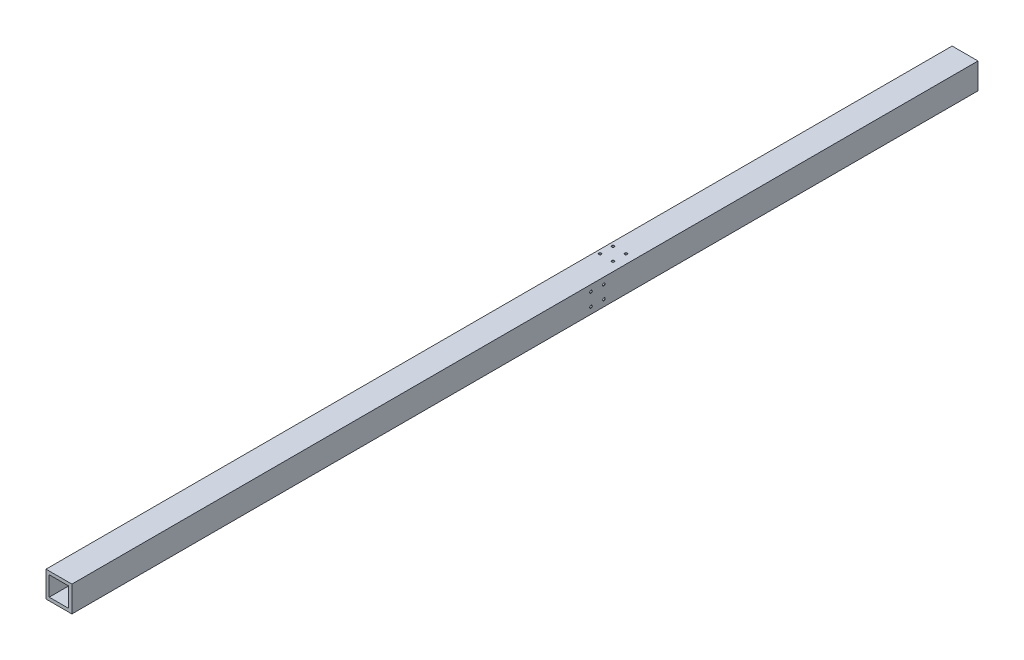
SolidWorks part; units mm, degrees
material "Д16Т ГОСТ 4784-74"
ref_plane "Спереди" through (0, 0, 0) normal (0, 0, 1) x (1, 0, 0)
ref_plane "Сверху" through (0, 0, 0) normal (0, 1, 0) x (1, 0, 0)
ref_plane "Справа" through (0, 0, 0) normal (1, 0, 0) x (0, 0, -1)
sketch "Эскиз1" plane through (0, 0, 0) normal (0, 0, 1) x (1, 0, 0)
  line L1 (0, 0) -> (40, 0)
  line L2 (0, 0) -> (0, 40)
  line L3 (0, 40) -> (40, 40)
  line L4 (40, 0) -> (40, 40)
  dimension "D1" = 40
extrude "Вытянуть-Тонкостенный1" add sketch "Эскиз1" along normal blind 1400 thin thin type one direction reverse wall 5
hole_wizard "Отверстие обработанное метчиком M41" positions "Эскиз3" profile "Эскиз2" tap size "M4" standard "DIN"
sketch "Эскиз3" plane through (0, 0, 0) normal (-1, 0, 0) x (0, 0, 1)
  line L0 (1400, 40) -> (1400, 0) construction
  line L1 (1400, 40) -> (0, 40) construction
  point P0 (1030, 30)
  point P11 (1010, 30)
  point P12 (1030, 10)
  point P13 (1010, 10)
  dimension "D1" = 370
  dimension "D2" = 10
  dimension "D3" = 2
  dimension "D4" = 2
sketch "Эскиз2" plane through (0, 30, 1030) normal (0, 1, 0) x (0, 0, 1)
  line L0 (0, 0) -> (0, 12.4914)
  line L1 (0, 12.4914) -> (1.65, 11.5)
  line L2 (1.65, 11.5) -> (1.65, 0.2165)
  line L3 (1.65, 0.2165) -> (2.025, 0)
  line L5 (2.025, 0) -> (0, 0)
  line L6 (-1.65, 0.2165) -> (-2.025, 0) construction
  line L10 (0, 12.4914) -> (-1.65, 11.5) construction
  line L11 (0, -6.35) -> (0, 107.95) construction
  dimension "Диаметр сверла" = 3.3
  dimension "Глубина сверла" = 11.5
  dimension "Диаметр передней зенковки" = 4.05
  dimension "Угол передней зенковки" = 120
  dimension "Угол заточки сверла" = 118
cosmetic thread "Отверстие резьбы1" parameters "D1"=5, "D2"=4
cosmetic thread "Отверстие резьбы2" parameters "D1"=5, "D2"=4
cosmetic thread "Отверстие резьбы3" parameters "D1"=5, "D2"=4
cosmetic thread "Отверстие резьбы4" parameters "D1"=5, "D2"=4
hole_wizard "Отверстие обработанное метчиком M42" positions "Эскиз5" profile "Эскиз4" tap size "M4" standard "DIN"
sketch "Эскиз5" plane through (40, 0, 0) normal (1, 0, 0) x (0, 0, -1)
  line L0 (-1400, 0) -> (-1400, 40) construction
  line L1 (-1400, 40) -> (0, 40) construction
  point P0 (-598, 30)
  point P9 (-578, 30)
  point P10 (-598, 10)
  point P11 (-578, 10)
  dimension "D1" = 802
  dimension "D2" = 10
  dimension "D3" = 2
  dimension "D4" = 2
sketch "Эскиз4" plane through (40, 30, 598) normal (0, 1, 0) x (0, 0, -1)
  line L0 (0, 0) -> (0, 12.4914)
  line L1 (0, 12.4914) -> (1.65, 11.5)
  line L2 (1.65, 11.5) -> (1.65, 0.2165)
  line L3 (1.65, 0.2165) -> (2.025, 0)
  line L5 (2.025, 0) -> (0, 0)
  line L6 (-1.65, 0.2165) -> (-2.025, 0) construction
  line L10 (0, 12.4914) -> (-1.65, 11.5) construction
  line L11 (0, -6.35) -> (0, 107.95) construction
  dimension "Диаметр сверла" = 3.3
  dimension "Глубина сверла" = 11.5
  dimension "Диаметр передней зенковки" = 4.05
  dimension "Угол передней зенковки" = 120
  dimension "Угол заточки сверла" = 118
cosmetic thread "Отверстие резьбы5" parameters "D1"=5, "D2"=4
cosmetic thread "Отверстие резьбы6" parameters "D1"=5, "D2"=4
cosmetic thread "Отверстие резьбы7" parameters "D1"=5, "D2"=4
cosmetic thread "Отверстие резьбы8" parameters "D1"=5, "D2"=4
hole_wizard "Отверстие обработанное метчиком M43" positions "Эскиз7" profile "Эскиз6" tap size "M4" standard "DIN"
sketch "Эскиз7" plane through (0, 0, 0) normal (0, -1, 0) x (1, 0, 0)
  line L0 (0, 1400) -> (40, 1400) construction
  line L1 (40, 1400) -> (40, 0) construction
  point P0 (30, 1030)
  point P10 (10, 1030)
  point P11 (30, 1010)
  point P12 (10, 1010)
  dimension "D1" = 370
  dimension "D2" = 10
  dimension "D3" = 2
  dimension "D4" = 2
sketch "Эскиз6" plane through (30, 0, 1030) normal (1, 0, 0) x (0, 0, -1)
  line L0 (0, 0) -> (0, 12.4914)
  line L1 (0, 12.4914) -> (1.65, 11.5)
  line L2 (1.65, 11.5) -> (1.65, 0.2165)
  line L3 (1.65, 0.2165) -> (2.025, 0)
  line L5 (2.025, 0) -> (0, 0)
  line L6 (-1.65, 0.2165) -> (-2.025, 0) construction
  line L10 (0, 12.4914) -> (-1.65, 11.5) construction
  line L11 (0, -6.35) -> (0, 107.95) construction
  dimension "Диаметр сверла" = 3.3
  dimension "Глубина сверла" = 11.5
  dimension "Диаметр передней зенковки" = 4.05
  dimension "Угол передней зенковки" = 120
  dimension "Угол заточки сверла" = 118
cosmetic thread "Отверстие резьбы9" parameters "D1"=5, "D2"=4
cosmetic thread "Отверстие резьбы10" parameters "D1"=5, "D2"=4
cosmetic thread "Отверстие резьбы11" parameters "D1"=5, "D2"=4
cosmetic thread "Отверстие резьбы12" parameters "D1"=5, "D2"=4
hole_wizard "Отверстие обработанное метчиком M44" positions "Эскиз9" profile "Эскиз8" tap size "M4" standard "DIN"
sketch "Эскиз9" plane through (0, 40, 0) normal (0, 1, 0) x (-1, 0, 0)
  line L0 (-40, 1400) -> (0, 1400) construction
  line L1 (0, 1400) -> (0, 0) construction
  point P0 (-6, 550)
  point P10 (-26, 550)
  point P11 (-6, 530)
  point P12 (-26, 530)
  dimension "D1" = 850
  dimension "D2" = 6
  dimension "D3" = 2
  dimension "D4" = 2
sketch "Эскиз8" plane through (6, 40, 550) normal (1, 0, 0) x (0, 0, 1)
  line L0 (0, 0) -> (0, 12.4914)
  line L1 (0, 12.4914) -> (1.65, 11.5)
  line L2 (1.65, 11.5) -> (1.65, 0.2165)
  line L3 (1.65, 0.2165) -> (2.025, 0)
  line L5 (2.025, 0) -> (0, 0)
  line L6 (-1.65, 0.2165) -> (-2.025, 0) construction
  line L10 (0, 12.4914) -> (-1.65, 11.5) construction
  line L11 (0, -6.35) -> (0, 107.95) construction
  dimension "Диаметр сверла" = 3.3
  dimension "Глубина сверла" = 11.5
  dimension "Диаметр передней зенковки" = 4.05
  dimension "Угол передней зенковки" = 120
  dimension "Угол заточки сверла" = 118
cosmetic thread "Отверстие резьбы13" parameters "D1"=5, "D2"=4
cosmetic thread "Отверстие резьбы14" parameters "D1"=5, "D2"=4
cosmetic thread "Отверстие резьбы15" parameters "D1"=5, "D2"=4
cosmetic thread "Отверстие резьбы16" parameters "D1"=5, "D2"=4
